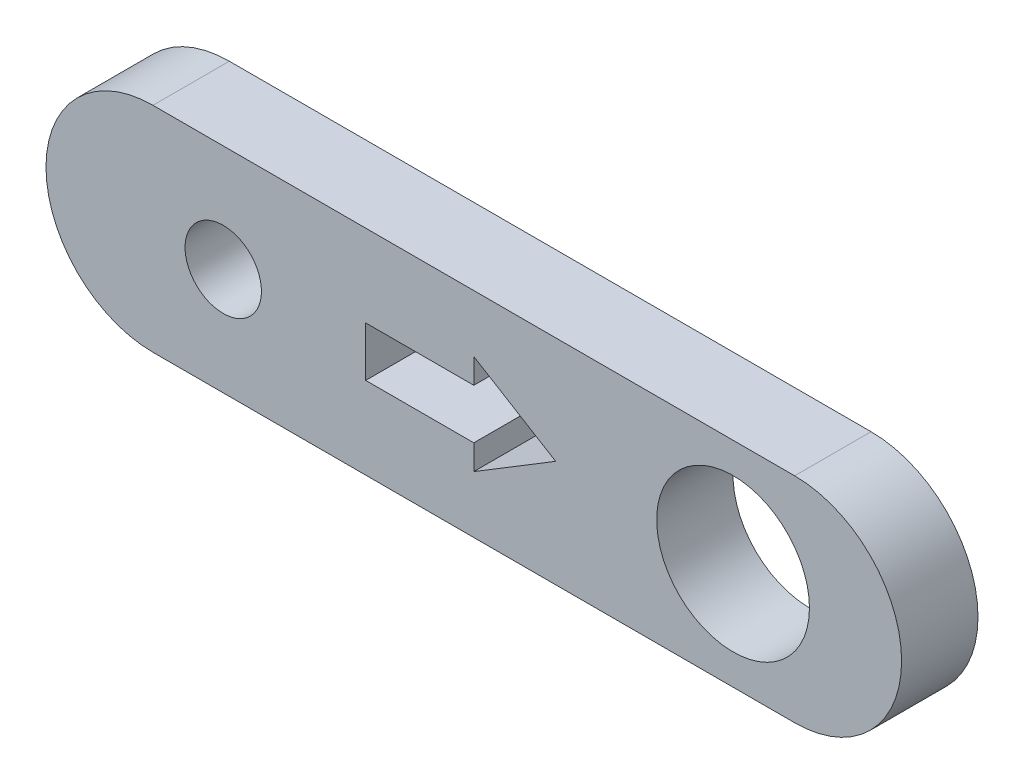
SolidWorks part; units mm, degrees
ref_plane "前基準面" through (0, 0, 0) normal (0, 0, 1) x (1, 0, 0)
ref_plane "上基準面" through (0, 0, 0) normal (0, 1, 0) x (1, 0, 0)
ref_plane "右基準面" through (0, 0, 0) normal (1, 0, 0) x (0, 0, -1)
sketch "草圖1" plane through (0, 0, 0) normal (0, 0, 1) x (1, 0, 0)
  line L0 (0, 0) -> (-42, 0) construction
  line L1 (0, -7) -> (-42, -7)
  line L2 (0, 7) -> (-42, 7)
  line L3 (-15.6415, 0) -> (-21, 3.26)
  line L4 (-42, 0) -> (-65.0077, 0) construction
  line L5 (-15.6415, 0) -> (-21, -3.26)
  line L6 (-21, 3.26) -> (-21, -3.26)
  line L7 (-21, 1.63) -> (-28.0745, 1.63)
  line L8 (-21, -1.63) -> (-28.0745, -1.63)
  line L9 (-28.0745, 1.63) -> (-28.0745, -1.63)
  arc A0 (0, -7) -> (0, 7) centre (0, 0) ccw
  arc A1 (-42, 7) -> (-42, -7) centre (-42, 0) ccw
  circle A2 centre (-37.3992, 0) radius 2.5
  circle A3 centre (-4.0314, 0) radius 5
  point P3 (-21, 0)
  dimension "D3" = 5
  dimension "D4" = 10
  dimension "D1" = 42
  dimension "D2" = 14
extrude "填料-伸長1" add sketch "草圖1" along normal blind 5 contours L2 A1 L1 A0 A3 A2 L9 L7 L6 L3 L5 L8
